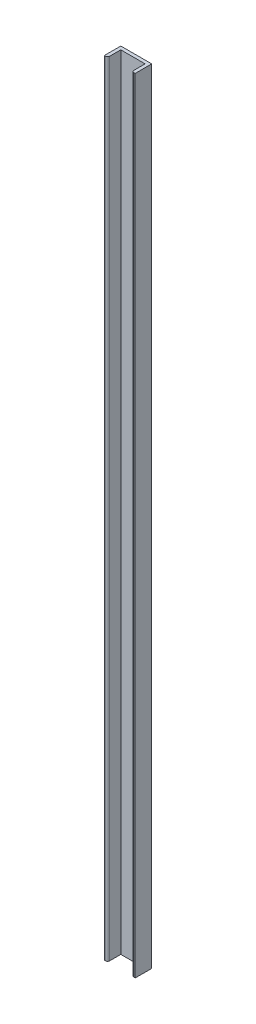
SolidWorks part; units mm, degrees
ref_plane "Front Plane" through (0, 0, 0) normal (0, 0, 1) x (1, 0, 0)
ref_plane "Top Plane" through (0, 0, 0) normal (0, 1, 0) x (1, 0, 0)
ref_plane "Right Plane" through (0, 0, 0) normal (1, 0, 0) x (0, 0, -1)
sketch "Sketch2" plane through (0, 0, 0) normal (1, 0, 0) x (0, 0, -1)
  line L0 (0, 0) -> (0, 1900)
  dimension "D1" = 1900
other "C channel 80 X 8(1)"
ref_plane "Plane1" through (0, 0, 0) normal (0, 1, 0) x (0, 0, 1)
sketch "Sketch11" plane through (0, 0, 0) normal (0, 1, 0) x (0, 0, 1)
  line L0 (0, -37.5) -> (0, 37.5)
  line L1 (0, 37.5) -> (40, 37.5)
  line L2 (40, 37.5) -> (40, 34.5)
  line L3 (35, 29.5) -> (8, 29.5)
  line L4 (8, 29.5) -> (8, -29.5)
  line L5 (8, -29.5) -> (35, -29.5)
  line L6 (40, -34.5) -> (40, -37.5)
  line L7 (40, -37.5) -> (0, -37.5)
  arc A0 (35, -29.5) -> (40, -34.5) centre (35, -34.5) cw
  arc A1 (40, 34.5) -> (35, 29.5) centre (35, 34.5) cw
  point P8 (0, 0)
  point P13 (40, 29.5)
  dimension "D4" = 8
  dimension "D5" = 5
  dimension "D2" = 40
  dimension "D1" = 75
  dimension "D3" = 8
